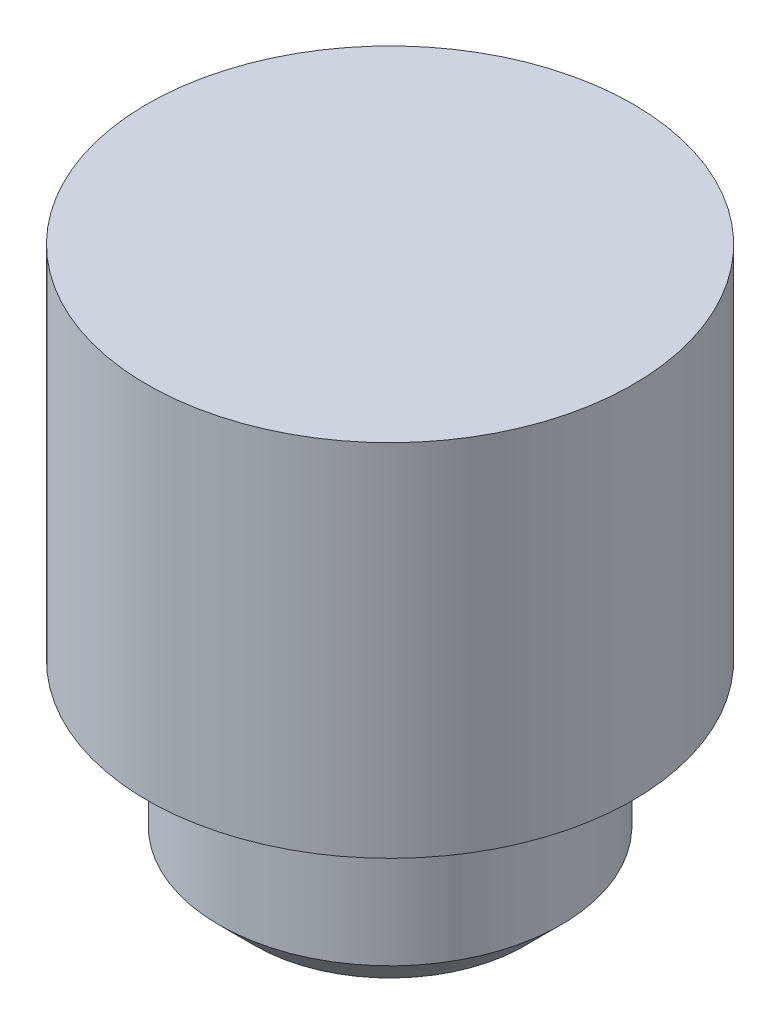
SolidWorks part; units mm, degrees
ref_plane "Front Plane" through (0, 0, 0) normal (0, 0, 1) x (1, 0, 0)
ref_plane "Top Plane" through (0, 0, 0) normal (0, 1, 0) x (1, 0, 0)
ref_plane "Right Plane" through (0, 0, 0) normal (1, 0, 0) x (0, 0, -1)
other "Default"
sketch "Sketch1" plane through (0, 0, 0) normal (0, 0, 1) x (1, 0, 0)
  line L0 (0, -27.6984) -> (0, 15.9524) construction
  line L1 (0, -7.5) -> (0, 7.5)
  line L2 (0, 7.5) -> (6.75, 7.5)
  line L3 (6.75, 7.5) -> (6.75, -2.5)
  line L4 (6.75, -2.5) -> (4.75, -2.5)
  line L5 (4.75, -2.5) -> (4.75, -7.5)
  line L6 (4.75, -7.5) -> (0, -7.5)
  dimension "D1" = 5
  dimension "D2" = 10
  dimension "ID" = 9.5
  dimension "D4" = 2
revolve "Revolve1" add sketch "Sketch1" angle 360 about L0
chamfer "Chamfer1" distance 1 angle 45 1 edges at (0, -7.5, -4.75)
